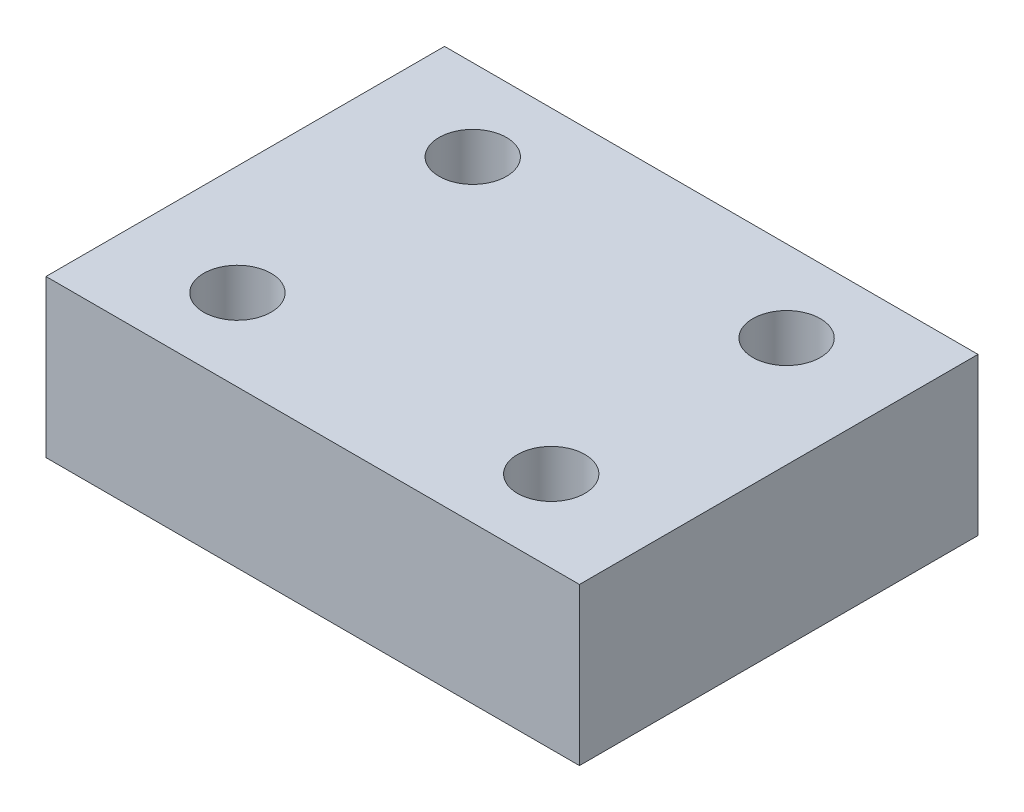
SolidWorks part; units mm, degrees
other "Markup1"
sketch "Sketch14" plane through (17, 0, 12.7) normal (0.0761, 0.7695, 0.6341) x (0.9929, 0, -0.1192)
material "6061-T6 (SS)"
ref_plane "Front Plane" through (0, 0, 0) normal (0, 0, 1) x (1, 0, 0)
ref_plane "Top Plane" through (0, 0, 0) normal (0, 1, 0) x (1, 0, 0)
ref_plane "Right Plane" through (0, 0, 0) normal (1, 0, 0) x (0, 0, -1)
sketch "Sketch1" plane through (0, 0, 0) normal (0, 0, 1) x (1, 0, 0)
  line L0 (-70, 30) -> (-70, 10) construction
  line L1 (-80, 40) -> (80, 40)
  line L2 (-80, 40) -> (-80, 0)
  line L3 (-80, 0) -> (80, 0)
  line L4 (80, 40) -> (80, 0)
  line L9 (37, 23) -> (43, 23) construction
  line L10 (37, 23) -> (37, 17) construction
  line L11 (37, 17) -> (43, 17) construction
  line L12 (43, 23) -> (43, 17) construction
  line L13 (0, 0) -> (0, 40) construction
  line L14 (37, 20) -> (43, 20) construction
  line L15 (40, 17) -> (40, 23) construction
  line L16 (22.5, 40) -> (22.5, 22.95)
  line L17 (22.5, 40) -> (57.5, 40) construction
  line L18 (22.5, 40) -> (22.5, 23) construction
  line L19 (22.5, 23) -> (57.5, 23) construction
  line L20 (57.5, 40) -> (57.5, 23) construction
  line L21 (22.5, 22.95) -> (37, 22.95)
  line L22 (37, 22.95) -> (37, 17)
  line L23 (37, 17) -> (43, 17)
  line L24 (43, 17) -> (43, 22.95)
  line L25 (43, 22.95) -> (57.5, 22.95)
  line L26 (57.5, 22.95) -> (57.5, 40)
  circle A0 centre (-70, 30) radius 2.5 construction
  circle A1 centre (-70, 10) radius 2.5 construction
  circle A2 centre (70, 10) radius 2.5 construction
  circle A3 centre (70, 30) radius 2.5 construction
  point P10 (0, 0)
  point P15 (80, 20)
  point P31 (40, 23)
  dimension "D8" = 5
  dimension "D10" = 10
  dimension "D2" = 160
  dimension "D3" = 40
  dimension "D4" = 40
  dimension "D5" = 35
  dimension "D6" = 6
  dimension "D7" = 20
  dimension "D9" = 10
  dimension "D11" = 0.05
extrude "Boss-Extrude1" [suppressed] add sketch "Sketch1" against normal blind 20
sketch "Sketch4" [suppressed] plane through (0, 0, 0) normal (0, -1, 0) x (1, 0, 0)
  line L0 (-60, -10) -> (60, -10) construction
  line L2 (-80, 0) -> (80, 0)
  line L3 (-80, 0) -> (-80, -20)
  line L4 (-80, -20) -> (80, -20)
  line L5 (80, 0) -> (80, -20)
  circle A0 centre (0, -10) radius 2.5 construction
  circle A1 centre (60, -10) radius 2.5 construction
  circle A2 centre (-60, -10) radius 2.5 construction
  point P6 (0, -10)
  point P14 (80, -10)
  dimension "D1" = 5
  dimension "D2" = 120
sketch "Sketch8" [suppressed] plane through (0, 22.95, 0) normal (0, 1, 0) x (1, 0, 0)
  line L8 (37, 0) -> (22.5, 0) construction
  line L9 (22.5, 0) -> (22.5, 20) construction
  line L10 (22.5, 20) -> (37, 20) construction
  line L11 (37, 20) -> (37, 0) construction
  line L12 (57.5, 0) -> (43, 0) construction
  line L13 (43, 0) -> (43, 20) construction
  line L14 (43, 20) -> (57.5, 20) construction
  line L15 (57.5, 20) -> (57.5, 0) construction
  line L16 (30, 5) -> (50, 5) construction
  line L17 (37, 20) -> (43, 20)
  line L18 (37, 20) -> (37, 0) construction
  line L19 (37, 20) -> (37, 0) construction
  line L20 (30, 5) -> (30, 15) construction
  line L21 (30, 15) -> (50, 15) construction
  line L22 (50, 15) -> (50, 5) construction
  circle A0 centre (50, 5) radius 2 construction
  circle A1 centre (30, 5) radius 2 construction
  circle A2 centre (30, 15) radius 2 construction
  circle A3 centre (50, 15) radius 2 construction
  point P4 (40, 5)
  point P5 (40, 20)
  point P17 (50, 10)
  point P18 (43, 10)
  dimension "D1" = 4
  dimension "D2" = 20
  dimension "D3" = 10
hole_wizard "Tap Drill for M4x0.7 Tap1" [suppressed] positions "3DSketch3" profile "Sketch9" hole size "M4x0.7" standard "ANSI Metric"
sketch3d "3DSketch3" [suppressed]
  point P10 (30, 22.95, -5)
  point P12 (50, 22.95, -5)
  point P19 (30, 22.95, -15)
  point P21 (50, 22.95, -15)
sketch "Sketch9" plane through (30, 22.95, -5) normal (1, 0, 0) x (0, 0, 1)
  line L0 (0, 0) -> (0, 5.9914)
  line L1 (0, 5.9914) -> (1.65, 5)
  line L2 (1.65, 5) -> (1.65, 0)
  line L5 (1.65, 0) -> (0, 0)
  line L10 (0, 5.9914) -> (-1.65, 5) construction
  line L11 (0, -6.35) -> (0, 107.95) construction
  dimension "Hole Dia." = 3.3
  dimension "Hole Depth" = 5
  dimension "Drill Angle" = 118
hole_wizard "Tap Drill for M5x0.8 Tap3" [suppressed] positions "3DSketch4" profile "Sketch10" hole size "M5x0.8" standard "ANSI Metric"
sketch3d "3DSketch4" [suppressed]
  point P0 (-70, 30, 0)
  point P2 (-70, 10, 0)
  point P4 (70, 10, 0)
  point P6 (70, 30, 0)
sketch "Sketch10" plane through (-70, 30, 0) normal (1, 0, 0) x (0, -1, 0)
  line L0 (0, 0) -> (0, 20)
  line L1 (0, 20) -> (2.1, 20)
  line L2 (2.1, 20) -> (2.1, 0)
  line L5 (2.1, 0) -> (0, 0)
  line L11 (0, -6.35) -> (0, 107.95) construction
  dimension "Thru Hole Dia." = 4.2
  dimension "Thru Hole Depth" = 20
hole_wizard "Tap Drill for M5x0.8 Tap2" [suppressed] positions "3DSketch2" profile "Sketch5" hole size "M5x0.8" standard "ANSI Metric"
sketch3d "3DSketch2" [suppressed]
  point P0 (-60, 0, -10)
  point P2 (0, 0, -10)
  point P4 (60, 0, -10)
sketch "Sketch5" plane through (-60, 0, -10) normal (1, 0, 0) x (0, 0, -1)
  line L0 (0, 0) -> (0, 8.2618)
  line L1 (0, 8.2618) -> (2.1, 7)
  line L2 (2.1, 7) -> (2.1, 0)
  line L5 (2.1, 0) -> (0, 0)
  line L10 (0, 8.2618) -> (-2.1, 7) construction
  line L11 (0, -6.35) -> (0, 107.95) construction
  dimension "Hole Dia." = 4.2
  dimension "Hole Depth" = 7
  dimension "Drill Angle" = 118
fillet "Fillet1" [suppressed] radius 1
ref_plane "Plane1" [suppressed] through (0, 0, -10) normal (0, 0, -1) x (-1, 0, 0)
sketch "Sketch12" plane through (0, 0, 0) normal (0, 1, 0) x (1, 0, 0)
  line L1 (-17, 12.7) -> (17, 12.7)
  line L2 (-17, 12.7) -> (-17, -12.7)
  line L3 (-17, -12.7) -> (17, -12.7)
  line L4 (17, 12.7) -> (17, -12.7)
  line L5 (-10, 7.5) -> (10, 7.5) construction
  line L6 (-10, 7.5) -> (-10, -7.5) construction
  line L7 (-10, -7.5) -> (10, -7.5) construction
  line L8 (10, 7.5) -> (10, -7.5) construction
  circle A0 centre (-10, 7.5) radius 2 construction
  circle A1 centre (-10, -7.5) radius 2 construction
  circle A2 centre (10, -7.5) radius 2 construction
  circle A3 centre (10, 7.5) radius 2 construction
  point P8 (0, 7.5)
  point P9 (0, 12.7)
  point P11 (-10, 0)
  point P12 (-17, 0)
  dimension "D3" = 4
  dimension "D1" = 34
  dimension "D2" = 25.4
  dimension "D4" = 15
  dimension "D5" = 20
extrude "Boss-Extrude2" add sketch "Sketch12" against normal blind 10
hole_wizard "M4 Clearance Hole1" positions "3DSketch5" profile "Sketch13" hole size "M4" standard "ANSI Metric" end condition through all
sketch3d "3DSketch5"
  point P0 (-10, 0, -7.5)
  point P2 (-10, 0, 7.5)
  point P4 (10, 0, 7.5)
  point P7 (10, 0, -7.5)
sketch "Sketch13" plane through (-10, 0, -7.5) normal (1, 0, 0) x (0, 0, 1)
  line L0 (0, 0) -> (0, 10)
  line L1 (0, 10) -> (2.15, 10)
  line L2 (2.15, 10) -> (2.15, 0)
  line L5 (2.15, 0) -> (0, 0)
  line L11 (0, -6.35) -> (0, 107.95) construction
  dimension "Thru Hole Dia." = 4.3
  dimension "Thru Hole Depth" = 10
